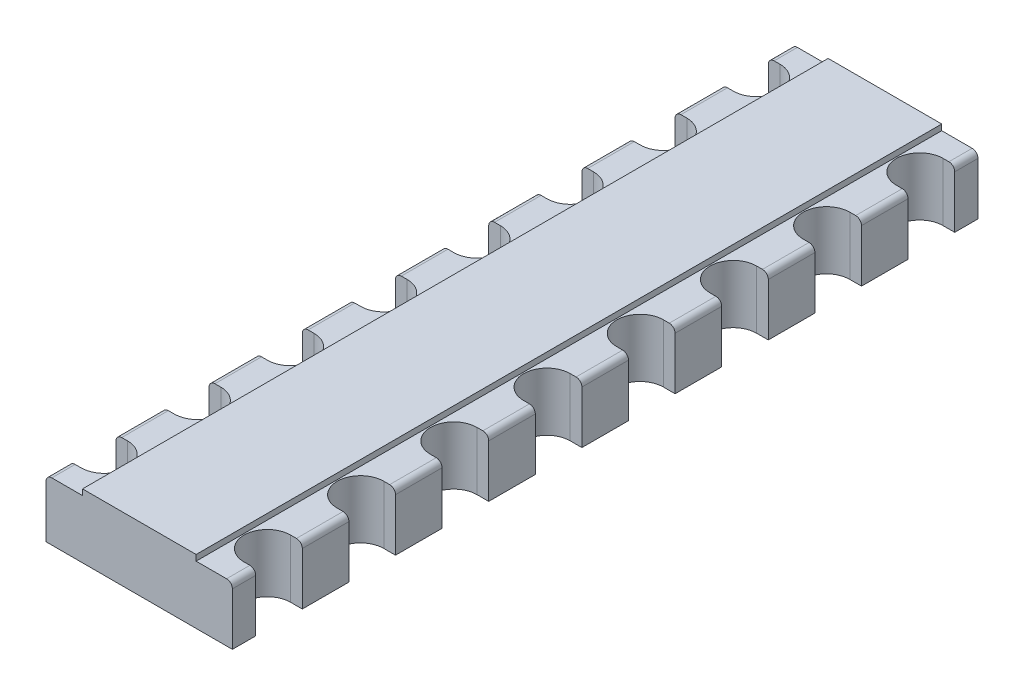
SolidWorks part; units mm, degrees
ref_plane "Front Plane" through (0, 0, 0) normal (0, 0, 1) x (1, 0, 0)
ref_plane "Top Plane" through (0, 0, 0) normal (0, 1, 0) x (1, 0, 0)
ref_plane "Right Plane" through (0, 0, 0) normal (1, 0, 0) x (0, 0, -1)
sketch "Sketch1" plane through (0, 0, 0) normal (0, 1, 0) x (1, 0, 0)
  line L0 (0, 4.095) -> (0, -2.2841) construction
  line L1 (-2.4335, 0) -> (1.9212, 0) construction
  line L3 (-0.8, 3.2) -> (-0.8, 3)
  line L4 (-0.8, 3) -> (-0.7, 3)
  line L5 (-0.7, 2.6) -> (-0.8, 2.6)
  line L6 (-0.8, 2.6) -> (-0.8, 2.2)
  line L7 (-0.8, 2.2) -> (-0.7, 2.2)
  line L8 (-0.7, 1.8) -> (-0.8, 1.8)
  line L30 (-0.8, 1.8) -> (-0.8, 1.4)
  line L31 (-0.8, 1.4) -> (-0.7, 1.4)
  line L32 (-0.7, 1) -> (-0.8, 1)
  line L33 (-0.8, 1) -> (-0.8, 0.6)
  line L34 (-0.8, 3) -> (-0.8, 2.6862) construction
  line L37 (-0.8, 3.2) -> (0.8, 3.2)
  line L49 (-0.8, 0.6) -> (-0.7, 0.6)
  line L50 (-0.7, 0.2) -> (-0.8, 0.2)
  line L74 (-0.8, 0.2) -> (-0.8, -0.2)
  line L75 (0.8, 3) -> (0.8, 2.6862) construction
  line L76 (0.8, 0.2) -> (0.8, -0.2)
  line L77 (0.7, 0.2) -> (0.8, 0.2)
  line L78 (0.8, 0.6) -> (0.7, 0.6)
  line L79 (0.8, 1) -> (0.8, 0.6)
  line L80 (0.7, 1) -> (0.8, 1)
  line L81 (0.8, 1.4) -> (0.7, 1.4)
  line L82 (0.8, 1.8) -> (0.8, 1.4)
  line L83 (0.7, 1.8) -> (0.8, 1.8)
  line L84 (0.8, 2.2) -> (0.7, 2.2)
  line L85 (0.8, 2.6) -> (0.8, 2.2)
  line L86 (0.7, 2.6) -> (0.8, 2.6)
  line L87 (0.8, 3) -> (0.7, 3)
  line L88 (0.8, 3.2) -> (0.8, 3)
  line L89 (0.8, -3) -> (0.8, -2.6862) construction
  line L90 (-0.8, -3) -> (-0.8, -2.6862) construction
  line L91 (0.8, -3.2) -> (0.8, -3)
  line L92 (0.8, -3) -> (0.7, -3)
  line L93 (0.7, -2.6) -> (0.8, -2.6)
  line L94 (0.8, -2.6) -> (0.8, -2.2)
  line L95 (0.8, -2.2) -> (0.7, -2.2)
  line L96 (0.7, -1.8) -> (0.8, -1.8)
  line L97 (0.8, -1.8) -> (0.8, -1.4)
  line L98 (0.8, -1.4) -> (0.7, -1.4)
  line L99 (0.7, -1) -> (0.8, -1)
  line L100 (0.8, -1) -> (0.8, -0.6)
  line L101 (0.8, -0.6) -> (0.7, -0.6)
  line L102 (0.7, -0.2) -> (0.8, -0.2)
  line L103 (-0.7, -0.2) -> (-0.8, -0.2)
  line L104 (-0.8, -0.6) -> (-0.7, -0.6)
  line L105 (-0.8, -3.2) -> (0.8, -3.2)
  line L106 (-0.8, -1) -> (-0.8, -0.6)
  line L107 (-0.7, -1) -> (-0.8, -1)
  line L108 (-0.8, -1.4) -> (-0.7, -1.4)
  line L109 (-0.8, -1.8) -> (-0.8, -1.4)
  line L110 (-0.7, -1.8) -> (-0.8, -1.8)
  line L111 (-0.8, -2.2) -> (-0.7, -2.2)
  line L112 (-0.8, -2.6) -> (-0.8, -2.2)
  line L113 (-0.7, -2.6) -> (-0.8, -2.6)
  line L114 (-0.8, -3) -> (-0.7, -3)
  line L115 (-0.8, -3.2) -> (-0.8, -3)
  arc A0 (-0.7, 3) -> (-0.7, 2.6) centre (-0.7, 2.8) cw
  arc A1 (-0.7, 2.2) -> (-0.7, 1.8) centre (-0.7, 2) cw
  arc A8 (-0.7, 1.4) -> (-0.7, 1) centre (-0.7, 1.2) cw
  arc A22 (-0.7, 0.6) -> (-0.7, 0.2) centre (-0.7, 0.4) cw
  arc A23 (0.7, 0.6) -> (0.7, 0.2) centre (0.7, 0.4) ccw
  arc A24 (0.7, 1.4) -> (0.7, 1) centre (0.7, 1.2) ccw
  arc A25 (0.7, 2.2) -> (0.7, 1.8) centre (0.7, 2) ccw
  arc A26 (0.7, 3) -> (0.7, 2.6) centre (0.7, 2.8) ccw
  arc A27 (0.7, -3) -> (0.7, -2.6) centre (0.7, -2.8) cw
  arc A28 (0.7, -2.2) -> (0.7, -1.8) centre (0.7, -2) cw
  arc A29 (0.7, -1.4) -> (0.7, -1) centre (0.7, -1.2) cw
  arc A30 (0.7, -0.6) -> (0.7, -0.2) centre (0.7, -0.4) cw
  arc A31 (-0.7, -0.6) -> (-0.7, -0.2) centre (-0.7, -0.4) ccw
  arc A32 (-0.7, -1.4) -> (-0.7, -1) centre (-0.7, -1.2) ccw
  arc A33 (-0.7, -2.2) -> (-0.7, -1.8) centre (-0.7, -2) ccw
  arc A34 (-0.7, -3) -> (-0.7, -2.6) centre (-0.7, -2.8) ccw
  point P23 (-0.75, 3)
  point P24 (0, 0)
  point P25 (0, 4.095)
  point P31 (0, 3.2)
  point P34 (0, 3.2)
  point P46 (0, 3.2)
  point P61 (-0.5, 2.8)
  point P95 (0.8, 0)
  point P96 (-0.8, 0)
  point P103 (0, -3.2)
  dimension "D4" = 0.8
  dimension "D1" = 2.8
  dimension "D2" = 0.8
  dimension "D3" = 3.2
  dimension "D5" = 0.4
  dimension "D6" = 0.3
extrude "Boss-Extrude1" add sketch "Sketch1" along normal blind 0.5
sketch "Sketch2" plane through (0, 0.5, 0) normal (0, 1, 0) x (1, 0, 0)
  line L0 (0.8, 3.2) -> (-0.8, 3.2) construction
  line L1 (-0.4864, -3.2) -> (0.4886, -3.2)
  line L2 (-0.4864, -3.2) -> (-0.4864, 3.2)
  line L3 (-0.4864, 3.2) -> (0.4886, 3.2)
  line L4 (0.4886, -3.2) -> (0.4886, 3.2)
  line L5 (-0.8, -3.2) -> (0.8, -3.2) construction
extrude "Boss-Extrude2" add sketch "Sketch2" along normal blind 0.05
fillet "Fillet2" radius 0.05 18 edges at (-0.8, 0.5, -1.6) (-0.8, 0.5, -2.4) (-0.8, 0.5, -3.1) (-0.8, 0.5, -0.8) (0.8, 0.5, -3.1) (0.8, 0.5, -2.4) (0.8, 0.5, -1.6) (0.8, 0.5, -0.8) (0.8, 0.5, 0) (0.8, 0.5, 0.8) (0.8, 0.5, 1.6) (0.8, 0.5, 2.4) (0.8, 0.5, 3.1) (-0.8, 0.5, 3.1) (-0.8, 0.5, 2.4) (-0.8, 0.5, 1.6) (-0.8, 0.5, 0.8) (-0.8, 0.5, 0)
